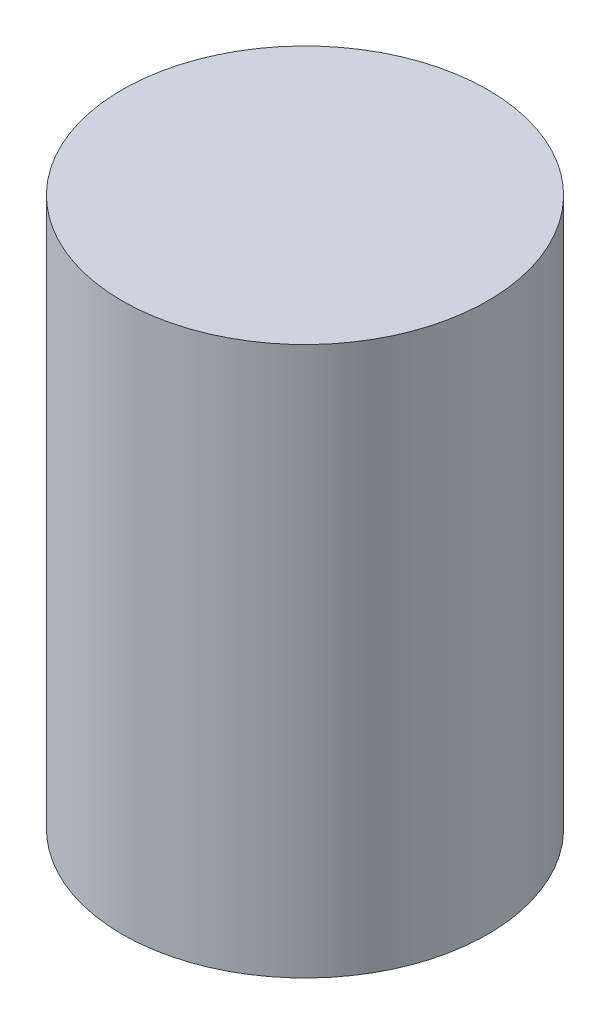
SolidWorks part; units mm, degrees
ref_plane "Front Plane" through (0, 0, 0) normal (0, 0, 1) x (1, 0, 0)
ref_plane "Top Plane" through (0, 0, 0) normal (0, 1, 0) x (1, 0, 0)
ref_plane "Right Plane" through (0, 0, 0) normal (1, 0, 0) x (0, 0, -1)
other "Configuration Table"
sketch "Sketch1" plane through (0, 0, 0) normal (0, 1, 0) x (1, 0, 0)
  circle A0 centre (185, 300) radius 150
extrude "PRESS_cop_kovasi_30L_D300" add sketch "Sketch1" along normal blind 450 from offset 1320 separate body
